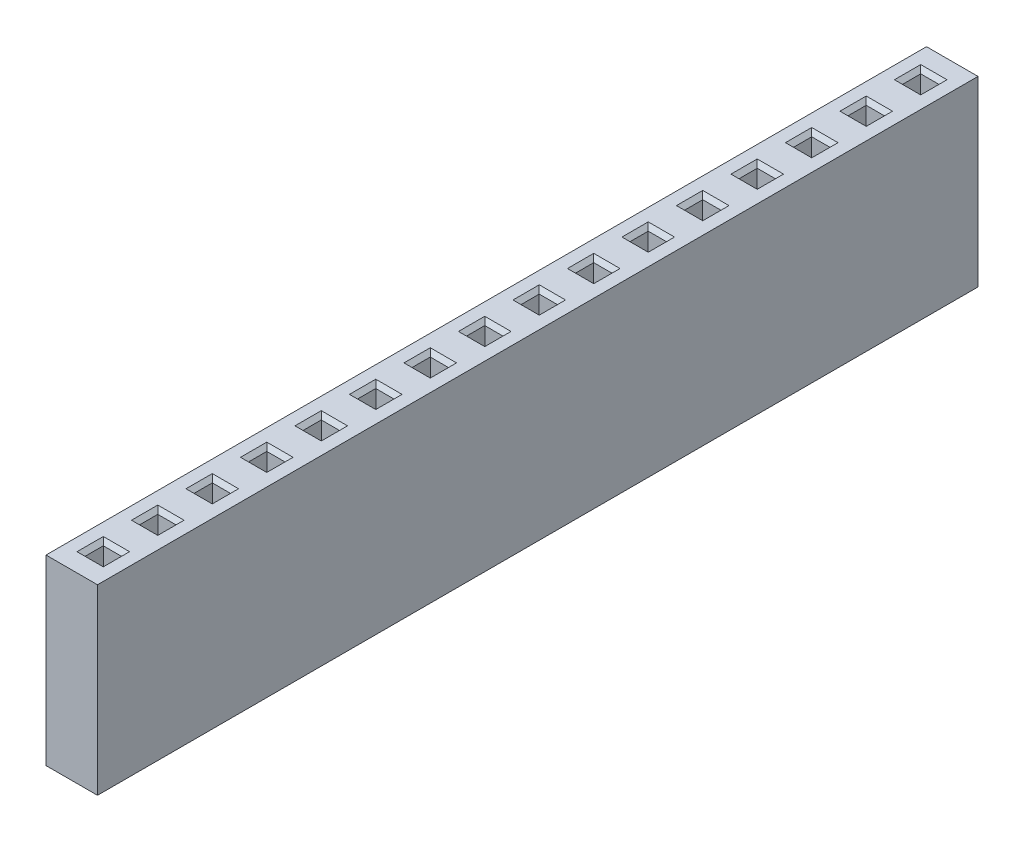
SolidWorks part; units mm, degrees
ref_plane "Front Plane" through (0, 0, 0) normal (0, 0, 1) x (1, 0, 0)
ref_plane "Top Plane" through (0, 0, 0) normal (0, 1, 0) x (1, 0, 0)
ref_plane "Right Plane" through (0, 0, 0) normal (1, 0, 0) x (0, 0, -1)
sketch "Sketch1" plane through (0, 0, 0) normal (1, 0, 0) x (0, 0, -1)
  line L1 (-20.52, -4.25) -> (20.52, -4.25)
  line L2 (-20.52, -4.25) -> (-20.52, 4.25)
  line L3 (-20.52, 4.25) -> (20.52, 4.25)
  line L4 (20.52, -4.25) -> (20.52, 4.25)
  line L5 (-20.52, -4.25) -> (20.52, 4.25) construction
  line L6 (-20.52, 4.25) -> (20.52, -4.25) construction
  point P0 (0, 0)
  dimension "D1" = 8.5
  dimension "D2" = 41.04
extrude "Boss-Extrude1" add sketch "Sketch1" along normal blind 2.4
sketch "Sketch3" plane through (0, 4.25, 0) normal (0, 1, 0) x (1, 0, 0)
  line L0 (1.2, 20.52) -> (1.2, -20.52) construction
  line L1 (2.4, 20.52) -> (0, 20.52) construction
  line L2 (2.4, -20.52) -> (0, -20.52) construction
  line L4 (0.775, -19.475) -> (1.625, -19.475)
  line L5 (0.775, -19.475) -> (0.775, -18.625)
  line L6 (0.775, -18.625) -> (1.625, -18.625)
  line L7 (1.625, -19.475) -> (1.625, -18.625)
  line L8 (0.775, -19.475) -> (1.625, -18.625) construction
  line L9 (0.775, -18.625) -> (1.625, -19.475) construction
  line L10 (0.4, -19.85) -> (2, -19.85)
  line L11 (0.4, -19.85) -> (0.4, -18.25)
  line L12 (0.4, -18.25) -> (2, -18.25)
  line L13 (2, -19.85) -> (2, -18.25)
  line L14 (0.4, -19.85) -> (2, -18.25) construction
  line L15 (0.4, -18.25) -> (2, -19.85) construction
  point P6 (1.2, -19.05)
  point P11 (1.2, -19.05)
  dimension "D1" = 0.85
  dimension "D2" = 0.85
  dimension "D3" = 1.47
  dimension "D4" = 1.6
  dimension "D5" = 1.6
extrude "Cut-Extrude2" cut sketch "Sketch3" against normal through all contours L5 L4 L7 L6
chamfer "Chamfer1" distance 0.1875 4 edges at (1.2, 4.25, 19.475) (1.625, 4.25, 19.05) (1.2, 4.25, 18.625) (0.775, 4.25, 19.05)
pattern_linear "LPattern2" count 16 spacing 2.54 along (0, 0, -1) of "Chamfer1", "Cut-Extrude2"
